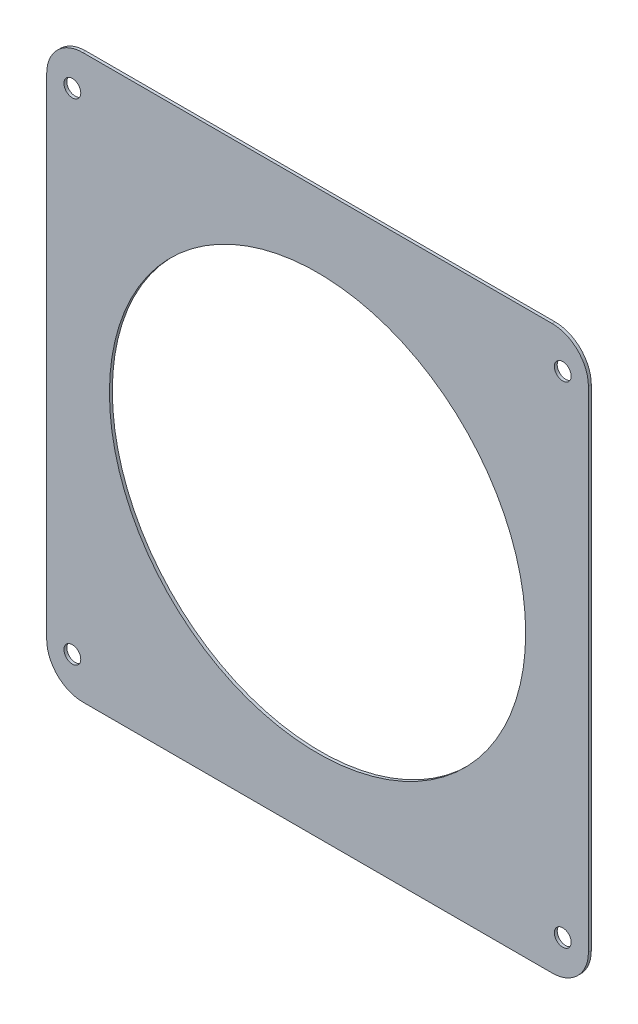
SolidWorks part; units mm, degrees
ref_plane "Front Plane" through (0, 0, 0) normal (0, 0, 1) x (1, 0, 0)
ref_plane "Top Plane" through (0, 0, 0) normal (0, 1, 0) x (1, 0, 0)
ref_plane "Right Plane" through (0, 0, 0) normal (1, 0, 0) x (0, 0, -1)
sketch "Sketch2" plane through (0, 0, 0) normal (0, 0, 1) x (1, 0, 0)
  line L0 (-25, 25) -> (25, 25) construction
  line L1 (0, 36.5) -> (0, -49.325) construction
  line L3 (-47.5, 49.325) -> (47.5, 49.325)
  line L4 (-47.5, 49.325) -> (-47.5, -49.325)
  line L5 (-47.5, -49.325) -> (47.5, -49.325)
  line L6 (47.5, 49.325) -> (47.5, -49.325)
  line L7 (-47.5, 49.325) -> (47.5, -49.325) construction
  line L8 (-47.5, -49.325) -> (47.5, 49.325) construction
  line L9 (-43, 43) -> (43, 43) construction
  line L10 (25, 25) -> (25, -25) construction
  line L11 (25, -25) -> (-25, -25) construction
  line L12 (-25, -25) -> (-25, 25) construction
  line L13 (-43, 43) -> (-43, -43) construction
  line L30 (-43, -43) -> (43, -43) construction
  line L31 (43, 43) -> (43, -43) construction
  line L32 (0, -43) -> (0, 43) construction
  line L33 (-43, 0) -> (43, 0) construction
  circle A0 centre (0, 0) radius 36.5
  circle A15 centre (-43, 43) radius 1.475
  circle A16 centre (43, 43) radius 1.475
  circle A17 centre (43, -43) radius 1.475
  circle A18 centre (-43, -43) radius 1.475
  point P16 (0, 25)
  point P17 (25, 0)
  dimension "D1" = 73
  dimension "D4" = 2.95
  dimension "D6" = 86
  dimension "D2" = 50
  dimension "D3" = 95
  dimension "D5" = 86
  dimension "D10" = 98.65
extrude "Boss-Extrude1" add sketch "Sketch2" along normal blind 0.508
fillet "Fillet1" radius 6.35 4 edges at (-47.5, 49.325, 0.254) (47.5, 49.325, 0.254) (47.5, -49.325, 0.254) (-47.5, -49.325, 0.254)
